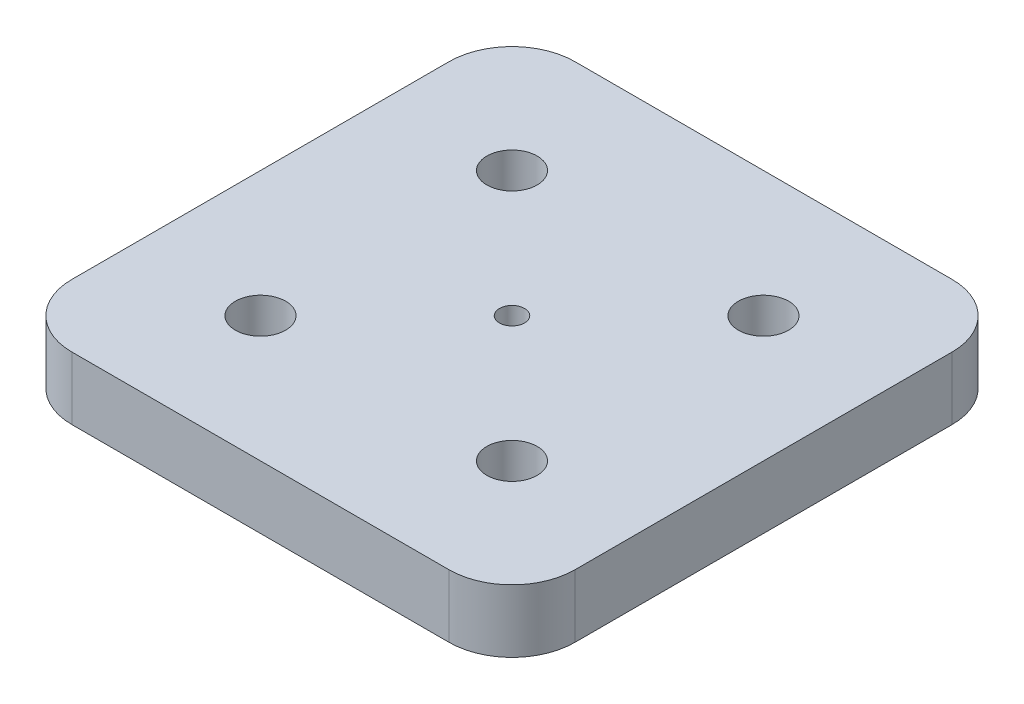
SolidWorks part; units mm, degrees
ref_plane "Front Plane" through (0, 0, 0) normal (0, 0, 1) x (1, 0, 0)
ref_plane "Top Plane" through (0, 0, 0) normal (0, 1, 0) x (1, 0, 0)
ref_plane "Right Plane" through (0, 0, 0) normal (1, 0, 0) x (0, 0, -1)
sketch "Sketch1" plane through (0, 0, 0) normal (0, 1, 0) x (1, 0, 0)
  line L0 (-21.8182, 20) -> (73.2867, 20) construction
  line L1 (0, 0) -> (40, 0)
  line L2 (0, 0) -> (0, 40)
  line L3 (0, 40) -> (40, 40)
  line L4 (40, 0) -> (40, 40)
  line L5 (20, 48.7552) -> (20, -11.3824) construction
  circle A0 centre (10, 30) radius 2
  circle A1 centre (30, 30) radius 2
  circle A2 centre (30, 10) radius 2
  circle A3 centre (10, 10) radius 2
  circle A4 centre (20, 20) radius 1
  point P7 (0, 20)
  dimension "D3" = 10
  dimension "D1" = 40
  dimension "D2" = 40
  dimension "D4" = 10
extrude "Boss-Extrude1" add sketch "Sketch1" along normal blind 5
fillet "Fillet1" radius 5 4 edges at (0, 2.5, 0) (40, 2.5, 0) (40, 2.5, -40) (0, 2.5, -40)
